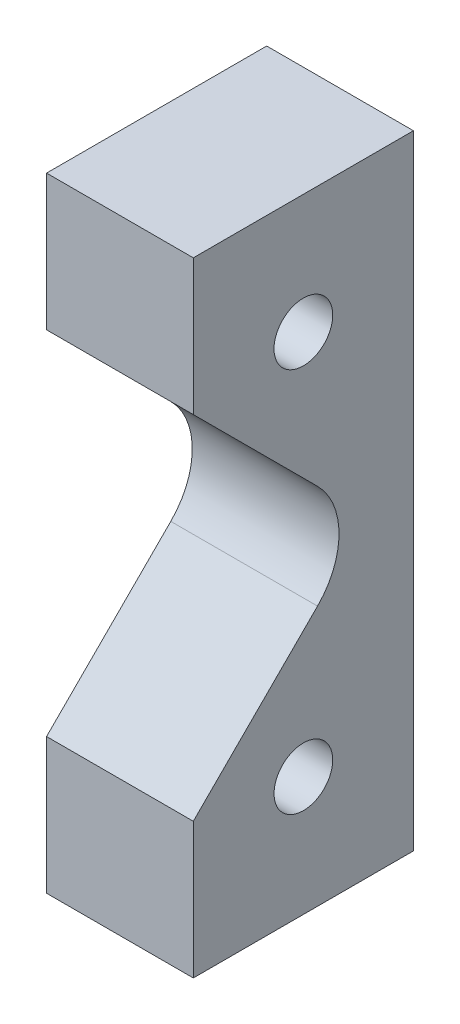
SolidWorks part; units mm, degrees
ref_plane "前视基准面" through (0, 0, 0) normal (0, 0, 1) x (1, 0, 0)
ref_plane "上视基准面" through (0, 0, 0) normal (0, 1, 0) x (1, 0, 0)
ref_plane "右视基准面" through (0, 0, 0) normal (1, 0, 0) x (0, 0, -1)
sketch "草图1" plane through (0, 0, 0) normal (1, 0, 0) x (0, 0, -1)
  line L0 (-15, 24) -> (1.9289, 7.0711)
  line L1 (15, -42.5) -> (-15, -42.5)
  line L2 (15, -42.5) -> (15, 42.5)
  line L3 (15, 42.5) -> (-15, 42.5)
  line L4 (-15, -42.5) -> (-15, -24)
  line L5 (-15, -24) -> (1.9289, -7.0711)
  line L8 (-15, 24) -> (-15, 42.5)
  arc A0 (1.9289, -7.0711) -> (1.9289, 7.0711) centre (-5.1421, 0) ccw
  point P0 (0, 0)
  dimension "D5" = 10
  dimension "D1" = 30
  dimension "D2" = 85
  dimension "D3" = 225
  dimension "D4" = 225
extrude "凸台-拉伸1" add sketch "草图1" along normal blind 20
sketch "草图3" plane through (0, 0, 0) normal (-1, 0, 0) x (0, 0, 1)
  line L0 (-38.505, 0) -> (41.0161, 0) construction
  line L1 (15, 42.5) -> (15, 24) construction
  circle A0 centre (0, 26.25) radius 4
  circle A1 centre (0, -26.25) radius 4
  dimension "D1" = 8
  dimension "D2" = 15
  dimension "D3" = 26.25
extrude "切除-拉伸1" cut sketch "草图3" against normal blind 20
